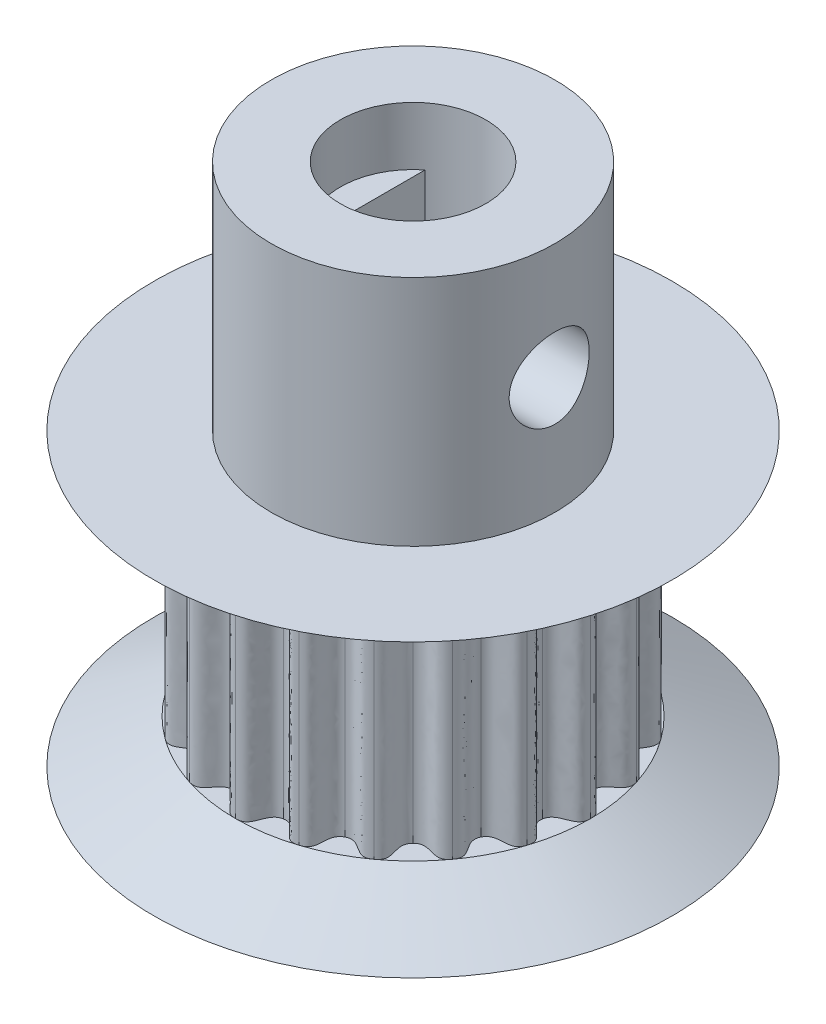
SolidWorks part; units mm, degrees
ref_plane "Front Plane" through (0, 0, 0) normal (0, 0, 1) x (1, 0, 0)
ref_plane "Top Plane" through (0, 0, 0) normal (0, 1, 0) x (1, 0, 0)
ref_plane "Right Plane" through (0, 0, 0) normal (1, 0, 0) x (0, 0, -1)
sketch "Sketch2" plane through (0, 0, 0) normal (0, 1, 0) x (1, 0, 0)
  line L0 (0, 0) -> (0, 6.1) construction
  line L1 (0, 0) -> (-0.9543, 6.0249) construction
  line L2 (0, 0) -> (0.9543, 6.0249) construction
  circle A0 centre (0, 0) radius 6.1 construction
  circle A1 centre (0, 0) radius 5.35 construction
  spline S0 degree 3 poles (0, 6.1) (0.153, 6.1) (0.4902, 5.9418) (0.4716, 5.342) (0.8369, 5.2841) knots 0 0 0 0 0.268003 1 1 1 1
  spline S1 degree 3 poles (0, 6.1) (-0.153, 6.1) (-0.4902, 5.9418) (-0.4716, 5.342) (-0.8369, 5.2841) knots 0 0 0 0 0.268003 1 1 1 1
  spline S2 degree 3 poles (1.885, 5.8014) (1.7395, 5.8487) (1.3699, 5.8025) (1.2022, 5.2263) (0.8369, 5.2841) knots 0 0 0 0 0.268003 1 1 1 1
  spline S3 degree 3 poles (1.885, 5.8014) (2.0305, 5.7542) (2.3024, 5.4995) (2.0993, 4.9348) (2.4288, 4.7669) knots 0 0 0 0 0.268003 1 1 1 1
  spline S4 degree 3 poles (3.5855, 4.935) (3.4617, 5.0249) (3.0959, 5.0952) (2.7584, 4.599) (2.4288, 4.7669) knots 0 0 0 0 0.268003 1 1 1 1
  spline S5 degree 3 poles (3.5855, 4.935) (3.7093, 4.8451) (3.8891, 4.5188) (3.5215, 4.0445) (3.783, 3.783) knots 0 0 0 0 0.268003 1 1 1 1
  spline S6 degree 3 poles (4.935, 3.5855) (4.8451, 3.7093) (4.5188, 3.8891) (4.0445, 3.5215) (3.783, 3.783) knots 0 0 0 0 0.268003 1 1 1 1
  spline S7 degree 3 poles (4.935, 3.5855) (5.0249, 3.4617) (5.0952, 3.0959) (4.599, 2.7584) (4.7669, 2.4288) knots 0 0 0 0 0.268003 1 1 1 1
  spline S8 degree 3 poles (5.8014, 1.885) (5.7542, 2.0305) (5.4995, 2.3024) (4.9348, 2.0993) (4.7669, 2.4288) knots 0 0 0 0 0.268003 1 1 1 1
  spline S9 degree 3 poles (5.8014, 1.885) (5.8487, 1.7395) (5.8025, 1.3699) (5.2263, 1.2022) (5.2841, 0.8369) knots 0 0 0 0 0.268003 1 1 1 1
  spline S10 degree 3 poles (6.1, 0) (6.1, 0.153) (5.9418, 0.4902) (5.342, 0.4716) (5.2841, 0.8369) knots 0 0 0 0 0.268003 1 1 1 1
  spline S11 degree 3 poles (6.1, 0) (6.1, -0.153) (5.9418, -0.4902) (5.342, -0.4716) (5.2841, -0.8369) knots 0 0 0 0 0.268003 1 1 1 1
  spline S12 degree 3 poles (5.8014, -1.885) (5.8487, -1.7395) (5.8025, -1.3699) (5.2263, -1.2022) (5.2841, -0.8369) knots 0 0 0 0 0.268003 1 1 1 1
  spline S13 degree 3 poles (5.8014, -1.885) (5.7542, -2.0305) (5.4995, -2.3024) (4.9348, -2.0993) (4.7669, -2.4288) knots 0 0 0 0 0.268003 1 1 1 1
  spline S14 degree 3 poles (4.935, -3.5855) (5.0249, -3.4617) (5.0952, -3.0959) (4.599, -2.7584) (4.7669, -2.4288) knots 0 0 0 0 0.268003 1 1 1 1
  spline S15 degree 3 poles (4.935, -3.5855) (4.8451, -3.7093) (4.5188, -3.8891) (4.0445, -3.5215) (3.783, -3.783) knots 0 0 0 0 0.268003 1 1 1 1
  spline S16 degree 3 poles (3.5855, -4.935) (3.7093, -4.8451) (3.8891, -4.5188) (3.5215, -4.0445) (3.783, -3.783) knots 0 0 0 0 0.268003 1 1 1 1
  spline S17 degree 3 poles (3.5855, -4.935) (3.4617, -5.0249) (3.0959, -5.0952) (2.7584, -4.599) (2.4288, -4.7669) knots 0 0 0 0 0.268003 1 1 1 1
  spline S18 degree 3 poles (1.885, -5.8014) (2.0305, -5.7542) (2.3024, -5.4995) (2.0993, -4.9348) (2.4288, -4.7669) knots 0 0 0 0 0.268003 1 1 1 1
  spline S19 degree 3 poles (1.885, -5.8014) (1.7395, -5.8487) (1.3699, -5.8025) (1.2022, -5.2263) (0.8369, -5.2841) knots 0 0 0 0 0.268003 1 1 1 1
  spline S20 degree 3 poles (0, -6.1) (0.153, -6.1) (0.4902, -5.9418) (0.4716, -5.342) (0.8369, -5.2841) knots 0 0 0 0 0.268003 1 1 1 1
  spline S21 degree 3 poles (0, -6.1) (-0.153, -6.1) (-0.4902, -5.9418) (-0.4716, -5.342) (-0.8369, -5.2841) knots 0 0 0 0 0.268003 1 1 1 1
  spline S22 degree 3 poles (-1.885, -5.8014) (-1.7395, -5.8487) (-1.3699, -5.8025) (-1.2022, -5.2263) (-0.8369, -5.2841) knots 0 0 0 0 0.268003 1 1 1 1
  spline S23 degree 3 poles (-1.885, -5.8014) (-2.0305, -5.7542) (-2.3024, -5.4995) (-2.0993, -4.9348) (-2.4288, -4.7669) knots 0 0 0 0 0.268003 1 1 1 1
  spline S24 degree 3 poles (-3.5855, -4.935) (-3.4617, -5.0249) (-3.0959, -5.0952) (-2.7584, -4.599) (-2.4288, -4.7669) knots 0 0 0 0 0.268003 1 1 1 1
  spline S25 degree 3 poles (-3.5855, -4.935) (-3.7093, -4.8451) (-3.8891, -4.5188) (-3.5215, -4.0445) (-3.783, -3.783) knots 0 0 0 0 0.268003 1 1 1 1
  spline S26 degree 3 poles (-4.935, -3.5855) (-4.8451, -3.7093) (-4.5188, -3.8891) (-4.0445, -3.5215) (-3.783, -3.783) knots 0 0 0 0 0.268003 1 1 1 1
  spline S27 degree 3 poles (-4.935, -3.5855) (-5.0249, -3.4617) (-5.0952, -3.0959) (-4.599, -2.7584) (-4.7669, -2.4288) knots 0 0 0 0 0.268003 1 1 1 1
  spline S28 degree 3 poles (-5.8014, -1.885) (-5.7542, -2.0305) (-5.4995, -2.3024) (-4.9348, -2.0993) (-4.7669, -2.4288) knots 0 0 0 0 0.268003 1 1 1 1
  spline S29 degree 3 poles (-5.8014, -1.885) (-5.8487, -1.7395) (-5.8025, -1.3699) (-5.2263, -1.2022) (-5.2841, -0.8369) knots 0 0 0 0 0.268003 1 1 1 1
  spline S30 degree 3 poles (-6.1, 0) (-6.1, -0.153) (-5.9418, -0.4902) (-5.342, -0.4716) (-5.2841, -0.8369) knots 0 0 0 0 0.268003 1 1 1 1
  spline S31 degree 3 poles (-6.1, 0) (-6.1, 0.153) (-5.9418, 0.4902) (-5.342, 0.4716) (-5.2841, 0.8369) knots 0 0 0 0 0.268003 1 1 1 1
  spline S32 degree 3 poles (-5.8014, 1.885) (-5.8487, 1.7395) (-5.8025, 1.3699) (-5.2263, 1.2022) (-5.2841, 0.8369) knots 0 0 0 0 0.268003 1 1 1 1
  spline S33 degree 3 poles (-5.8014, 1.885) (-5.7542, 2.0305) (-5.4995, 2.3024) (-4.9348, 2.0993) (-4.7669, 2.4288) knots 0 0 0 0 0.268003 1 1 1 1
  spline S34 degree 3 poles (-4.935, 3.5855) (-5.0249, 3.4617) (-5.0952, 3.0959) (-4.599, 2.7584) (-4.7669, 2.4288) knots 0 0 0 0 0.268003 1 1 1 1
  spline S35 degree 3 poles (-4.935, 3.5855) (-4.8451, 3.7093) (-4.5188, 3.8891) (-4.0445, 3.5215) (-3.783, 3.783) knots 0 0 0 0 0.268003 1 1 1 1
  spline S36 degree 3 poles (-3.5855, 4.935) (-3.7093, 4.8451) (-3.8891, 4.5188) (-3.5215, 4.0445) (-3.783, 3.783) knots 0 0 0 0 0.268003 1 1 1 1
  spline S37 degree 3 poles (-3.5855, 4.935) (-3.4617, 5.0249) (-3.0959, 5.0952) (-2.7584, 4.599) (-2.4288, 4.7669) knots 0 0 0 0 0.268003 1 1 1 1
  spline S38 degree 3 poles (-1.885, 5.8014) (-2.0305, 5.7542) (-2.3024, 5.4995) (-2.0993, 4.9348) (-2.4288, 4.7669) knots 0 0 0 0 0.268003 1 1 1 1
  spline S39 degree 3 poles (-1.885, 5.8014) (-1.7395, 5.8487) (-1.3699, 5.8025) (-1.2022, 5.2263) (-0.8369, 5.2841) knots 0 0 0 0 0.268003 1 1 1 1
  point P148 (0, 0)
  dimension "D1" = 12.2
  dimension "D3" = 0.75
  dimension "D2" = 9
extrude "Boss-Extrude3" add sketch "Sketch2" along normal mid plane 7
sketch "Sketch3" plane through (0, -3.5, 0) normal (0, -1, 0) x (1, 0, 0)
  circle A0 centre (0, 0) radius 6.1
ref_plane "Plane1" through (0, -5, 0) normal (0, -1, 0) x (-1, 0, 0)
sketch "Sketch4" plane through (0, -5, 0) normal (0, -1, 0) x (-1, 0, 0)
  circle A0 centre (0, 0) radius 8.9
  dimension "D1" = 17.8
loft "Loft1" add profiles "Sketch4", "Sketch3"
mirror "Mirror1" about plane through (0, 0, 0) normal (0, 1, 0) of bodies 104
combine bodies "Combine1" operation type add bodies to combine 104 103 105
sketch "Sketch5" plane through (0, 5, 0) normal (0, 1, 0) x (1, 0, 0)
  line L0 (0, 2.5) -> (0, -2.5) construction
  line L1 (1.55, 1.9615) -> (1.55, -1.9615)
  line L2 (-1.55, 1.9615) -> (-1.55, -1.9615)
  circle A0 centre (0, 0) radius 2.5
  circle A1 centre (0, 0) radius 4.875
  dimension "D1" = 5
  dimension "D2" = 9.75
  dimension "D3" = 3.1
extrude "Boss-Extrude4" add sketch "Sketch5" along normal blind 8 contours A1 A0 | L2 A0 | L1 A0
sketch "Sketch6" plane through (-1.55, 0, 0) normal (1, 0, 0) x (0, 0, -1)
  line L0 (0, 5) -> (0, 13) construction
  line L1 (8.9, 5) -> (-8.9, 5) construction
  line L2 (4.875, 13) -> (-4.875, 13) construction
  circle A0 centre (0, 9) radius 1.375
  point P2 (0, 0)
  dimension "D1" = 2.75
extrude "Cut-Extrude1" cut sketch "Sketch6" along normal up to surface (6.2271 mm away)
sketch "Sketch7" plane through (0, 13, 0) normal (0, 1, 0) x (1, 0, 0)
  circle A0 centre (0, 0) radius 2.5
  arc A1 (1.55, 1.9615) -> (-1.55, 1.9615) centre (0, 0) ccw construction
extrude "Cut-Extrude2" cut sketch "Sketch7" against normal blind 2
